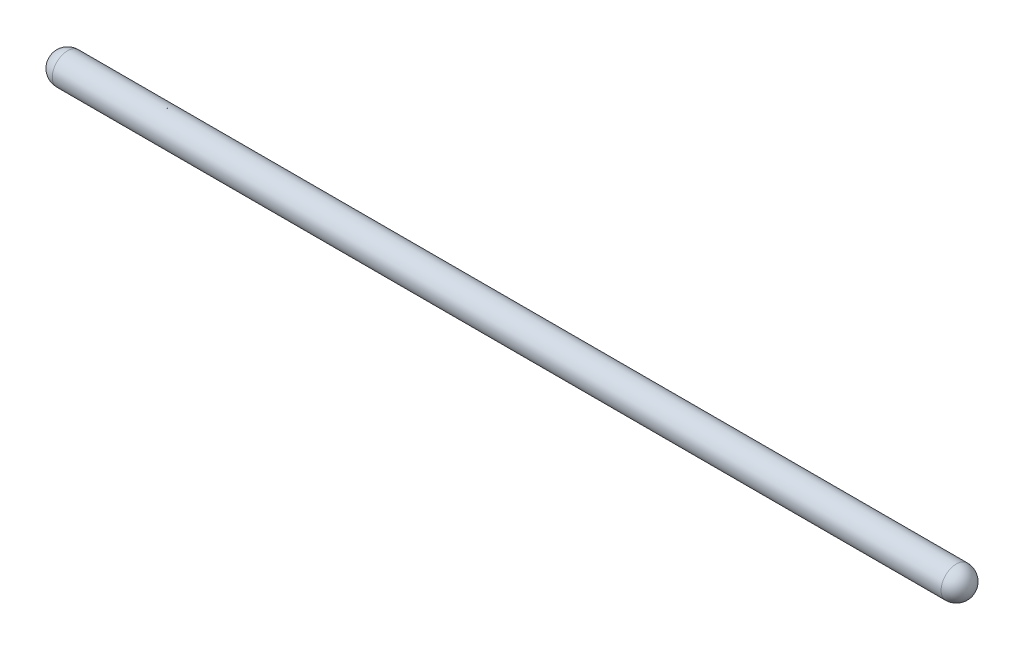
SolidWorks part; units mm, degrees
material "Brass"
ref_plane "Front Plane" through (0, 0, 0) normal (0, 0, 1) x (1, 0, 0)
ref_plane "Top Plane" through (0, 0, 0) normal (0, 1, 0) x (1, 0, 0)
ref_plane "Right Plane" through (0, 0, 0) normal (1, 0, 0) x (0, 0, -1)
sketch "Sketch1" plane through (0, 0, 0) normal (0, 0, 1) x (1, 0, 0)
  line L0 (0, 0) -> (150, 0) construction
  line L1 (2.5, 2.5) -> (147.5, 2.5)
  line L2 (150, 0) -> (0, 0)
  arc A0 (150, 0) -> (147.5, 2.5) centre (147.5, 0) ccw
  arc A1 (2.5, 2.5) -> (0, 0) centre (2.5, 0) ccw
revolve "Revolve1" add sketch "Sketch1" angle 360 about L0
